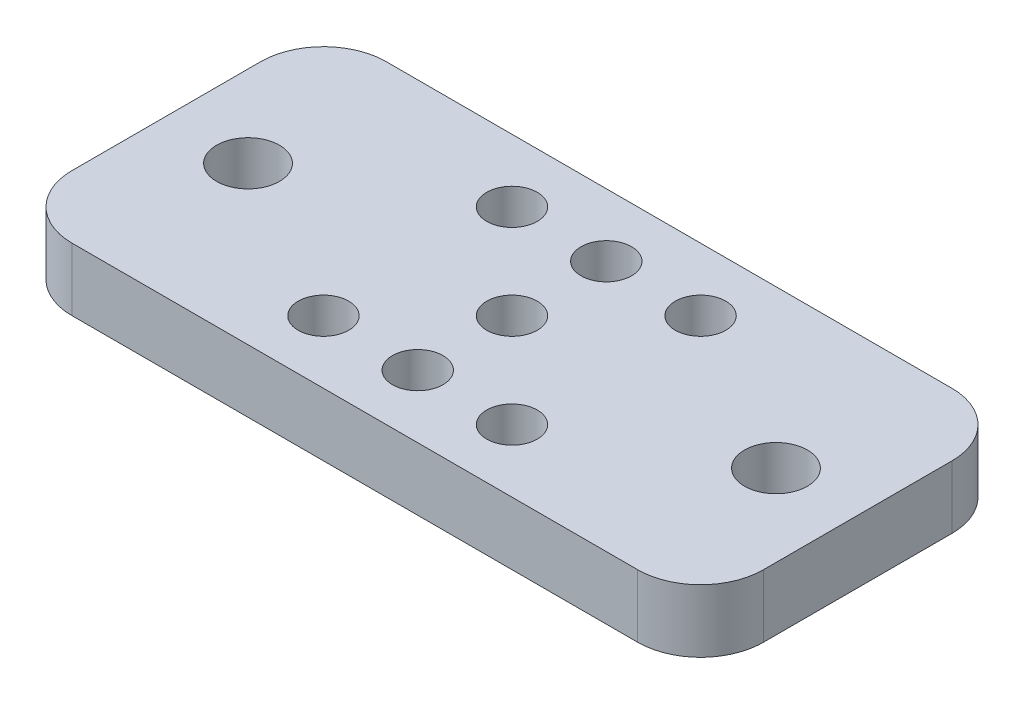
SolidWorks part; units mm, degrees
ref_plane "Front" through (0, 0, 0) normal (0, 0, 1) x (1, 0, 0)
ref_plane "Top" through (0, 0, 0) normal (0, 1, 0) x (1, 0, 0)
ref_plane "Right" through (0, 0, 0) normal (1, 0, 0) x (0, 0, -1)
sketch "Sketch1" plane through (0, 0, 0) normal (0, 1, 0) x (1, 0, 0)
  line B0 (-28.575, -15.875) -> (28.575, -15.875)
  line B1 (-34.925, 9.525) -> (-34.925, -9.525)
  line B2 (28.575, 15.875) -> (-28.575, 15.875)
  line B3 (34.925, -9.525) -> (34.925, 9.525)
  circle B4 centre (-9.525, -9.525) radius 2.5527
  circle B5 centre (-9.525, 9.525) radius 2.5527
  circle B6 centre (-26.67, 0) radius 3.175
  circle B7 centre (0, -9.525) radius 2.5527
  circle B8 centre (9.525, -9.525) radius 2.5527
  circle B9 centre (26.67, 0) radius 3.175
  circle B10 centre (9.525, 9.525) radius 2.5527
  circle B11 centre (0, 9.525) radius 2.5527
  circle B12 centre (0, 0) radius 2.5527
  spline B13 degree 2 poles (-34.925, -9.525) (-34.925, -10.1079) (-34.819, -10.6805) (-34.7064, -11.2885) (-34.4792, -11.8624) (-34.242, -12.4614) (-33.8899, -12.9998) (-33.5298, -13.5506) (-33.0651, -14.0151) (-32.5997, -14.4804) (-32.0498, -14.8399) (-31.5105, -15.1924) (-30.9124, -15.4292) (-30.3375, -15.6567) (-29.7305, -15.769) (-29.1573, -15.875) (-28.575, -15.875) knots 0 0 0 0.125 0.125 0.25 0.25 0.375 0.375 0.5 0.5 0.625 0.625 0.75 0.75 0.875 0.875 1 1 1
  spline B14 degree 2 poles (-28.575, 15.875) (-29.1579, 15.875) (-29.7305, 15.769) (-30.3385, 15.6564) (-30.9124, 15.4292) (-31.5114, 15.192) (-32.0498, 14.8399) (-32.6006, 14.4798) (-33.0651, 14.0151) (-33.5304, 13.5497) (-33.8899, 12.9998) (-34.2424, 12.4605) (-34.4792, 11.8624) (-34.7067, 11.2875) (-34.819, 10.6805) (-34.925, 10.1073) (-34.925, 9.525) knots 0 0 0 0.125 0.125 0.25 0.25 0.375 0.375 0.5 0.5 0.625 0.625 0.75 0.75 0.875 0.875 1 1 1
  spline B15 degree 2 poles (34.925, 9.525) (34.925, 10.1079) (34.819, 10.6805) (34.7064, 11.2885) (34.4792, 11.8624) (34.242, 12.4614) (33.8899, 12.9998) (33.5298, 13.5506) (33.0651, 14.0151) (32.5997, 14.4804) (32.0498, 14.8399) (31.5105, 15.1924) (30.9124, 15.4292) (30.3375, 15.6567) (29.7305, 15.769) (29.1573, 15.875) (28.575, 15.875) knots 0 0 0 0.125 0.125 0.25 0.25 0.375 0.375 0.5 0.5 0.625 0.625 0.75 0.75 0.875 0.875 1 1 1
  spline B16 degree 2 poles (28.575, -15.875) (29.1579, -15.875) (29.7305, -15.769) (30.3385, -15.6564) (30.9124, -15.4292) (31.5114, -15.192) (32.0498, -14.8399) (32.6006, -14.4798) (33.0651, -14.0151) (33.5304, -13.5497) (33.8899, -12.9998) (34.2424, -12.4605) (34.4792, -11.8624) (34.7067, -11.2875) (34.819, -10.6805) (34.925, -10.1073) (34.925, -9.525) knots 0 0 0 0.125 0.125 0.25 0.25 0.375 0.375 0.5 0.5 0.625 0.625 0.75 0.75 0.875 0.875 1 1 1
sketch_block_instance "Block1-1"
sketch_block "Block1"
extrude "Boss-Extrude2" add sketch "Sketch1" along normal mid plane 6.35
